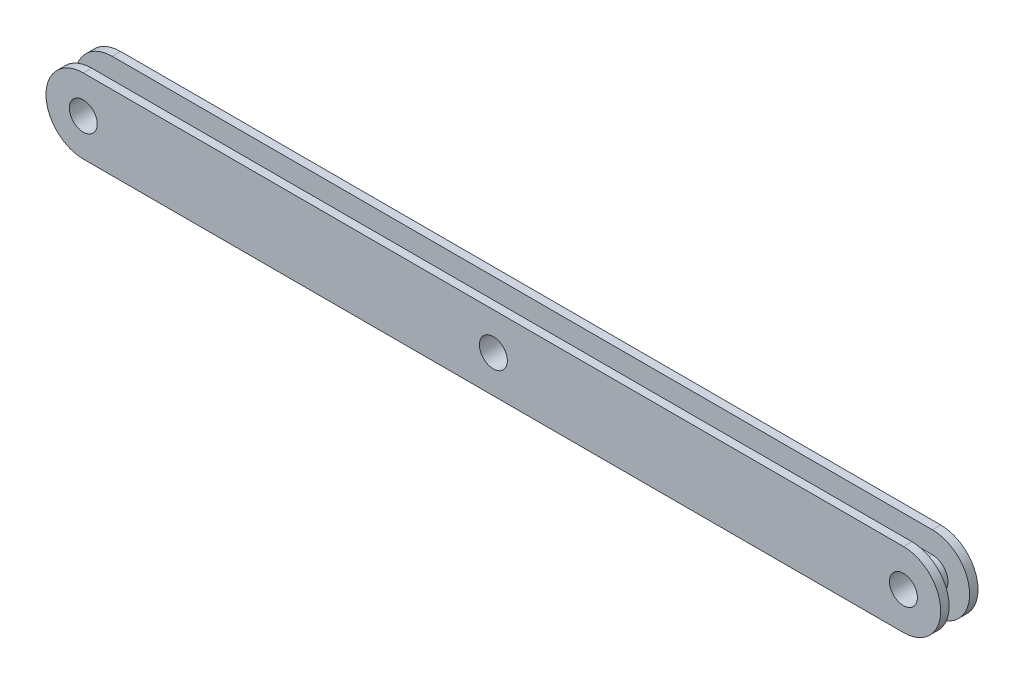
SolidWorks part; units mm, degrees
ref_plane "Plan de face" through (0, 0, 0) normal (0, 0, 1) x (1, 0, 0)
ref_plane "Plan de dessus" through (0, 0, 0) normal (0, 1, 0) x (1, 0, 0)
ref_plane "Plan de droite" through (0, 0, 0) normal (1, 0, 0) x (0, 0, -1)
sketch "Esquisse1" plane through (0, 0, 0) normal (0, 0, 1) x (1, 0, 0)
  line L4 (0, 0) -> (-152.4, 0)
  line L5 (-152.4, 0) -> (-152.4, 12.7)
  line L6 (-152.4, 12.7) -> (0, 12.7)
  line L7 (0, 12.7) -> (0, 0)
  dimension "D1" = 12.7
  dimension "D2" = 152.4
extrude "Boss.-Extru.1" add sketch "Esquisse1" against normal blind 6.35
sketch "Esquisse2" plane through (0, 0, 0) normal (0, 0, 1) x (1, 0, 0)
  line L0 (0, 12.7) -> (-152.4, 12.7) construction
  line L1 (-152.4, 0) -> (0, 0) construction
  line L2 (-152.4, 12.7) -> (-152.4, 0) construction
  line L3 (-6.35, 12.7) -> (0, 12.7)
  line L4 (0, 12.7) -> (0, 0)
  line L5 (0, 0) -> (0, 12.7) construction
  line L6 (0, 0) -> (-6.35, 0)
  line L7 (-146.05, 12.7) -> (-152.4, 12.7)
  line L8 (-152.4, 12.7) -> (-152.4, 0)
  line L9 (-152.4, 0) -> (-146.05, 0)
  circle A0 centre (-146.05, 6.35) radius 2.3813
  circle A1 centre (-6.35, 6.35) radius 2.3813
  circle A2 centre (-76.2, 6.35) radius 2.3813
  arc A3 (-146.05, 12.7) -> (-146.05, 0) centre (-146.05, 6.35) ccw
  arc A4 (-6.35, 12.7) -> (-6.35, 0) centre (-6.35, 6.35) cw
  line M1 (0, 0) -> (0, 12.7)
  line M2 (0, 12.7) -> (-152.4, 12.7)
  line M3 (-152.4, 12.7) -> (-152.4, 0)
  line M4 (-152.4, 0) -> (0, 0)
  dimension "D1" = 4.7625
  dimension "D4" = 4.7625
  dimension "D7" = 4.7625
  dimension "D2" = 6.35
  dimension "D3" = 6.35
  dimension "D5" = 6.35
  dimension "D6" = 6.35
  dimension "D8" = 69.85
extrude "Enlèv. mat.-Extru.1" cut sketch "Esquisse2" against normal through all contours A0 | A2 | A1 | A4 L4 M2 | A4 M1 M4 | A3 M2 M3 | A3 L8 M4
ref_plane "Plane1" through (0, 0, -3.175) normal (0, 0, 1) x (1, 0, 0)
ref_plane "Plane2" through (0, 6.35, 0) normal (0, 1, 0) x (1, 0, 0)
sketch "Sketch1" plane through (0, 6.35, 0) normal (0, 1, 0) x (1, 0, 0)
  line L0 (-146.05, 6.35) -> (-146.05, 0) construction
  line L1 (-6.35, 6.35) -> (-146.05, 6.35) construction
  line L2 (-6.35, 0) -> (-146.05, 0) construction
  line L3 (-146.05, 6.35) -> (-146.05, 0) construction
  line L4 (-148.4313, 6.35) -> (-148.4313, 0) construction
  line L5 (-146.05, 6.35) -> (-152.4, 6.35) construction
  line L6 (-152.4, 0) -> (-146.05, 0) construction
  line L7 (-152.4, 4.9225) -> (-150.5585, 4.9225)
  line L8 (-152.4, 6.35) -> (-152.4, 0) construction
  line L11 (-148.717, 4.9225) -> (-148.717, 1.4275)
  line L14 (-150.5585, 1.4275) -> (-152.4, 1.4275)
  line L15 (-152.4, 1.4275) -> (-152.4, 4.9225)
  line L16 (-150.5585, 4.9225) -> (-148.717, 4.9225)
  line L17 (-150.5585, 1.4275) -> (-148.717, 1.4275)
  line L18 (-152.4, 4.9225) -> (-166.5708, 4.9225)
  line L19 (-166.5708, 4.9225) -> (-166.5708, 1.4275)
  line L20 (-166.5708, 1.4275) -> (-152.4, 1.4275)
  point P18 (-148.4313, 3.175)
  point P21 (-148.717, 3.175)
  dimension "D1" = 2.3812
  dimension "D2" = 3.495
  dimension "D4" = 14.1708
  dimension "D5" = 1.8415
revolve "Cut-Revolve1" cut sketch "Sketch1" angle 180 mid plane about L0
ref_plane "Plane3" through (-76.2, 0, 0) normal (1, 0, 0) x (0, 0, -1)
mirror "Mirror1" about plane through (-76.2, 0, 0) normal (1, 0, 0) of "Cut-Revolve1"
sketch "Sketch2" plane through (0, 0, 0) normal (1, 0, 0) x (0, 0, -1)
  line L0 (1.4275, 9.017) -> (1.4275, 12.7) construction
  line L1 (1.4275, 9.017) -> (4.9225, 9.017)
  line L2 (1.4275, 9.017) -> (1.4275, 12.7)
  line L3 (1.4275, 12.7) -> (4.9225, 12.7)
  line L4 (4.9225, 9.017) -> (4.9225, 12.7)
  line L5 (4.9225, 12.7) -> (4.9225, 9.017) construction
  line L6 (4.9225, 12.7) -> (1.4275, 12.7) construction
  line L7 (4.9225, 9.017) -> (1.4275, 9.017) construction
  dimension "D1" = 3.495
extrude "Cut-Extrude1" cut sketch "Sketch2" against normal through all
mirror "Mirror2" about plane through (0, 6.35, 0) normal (0, 1, 0) of "Cut-Extrude1"
